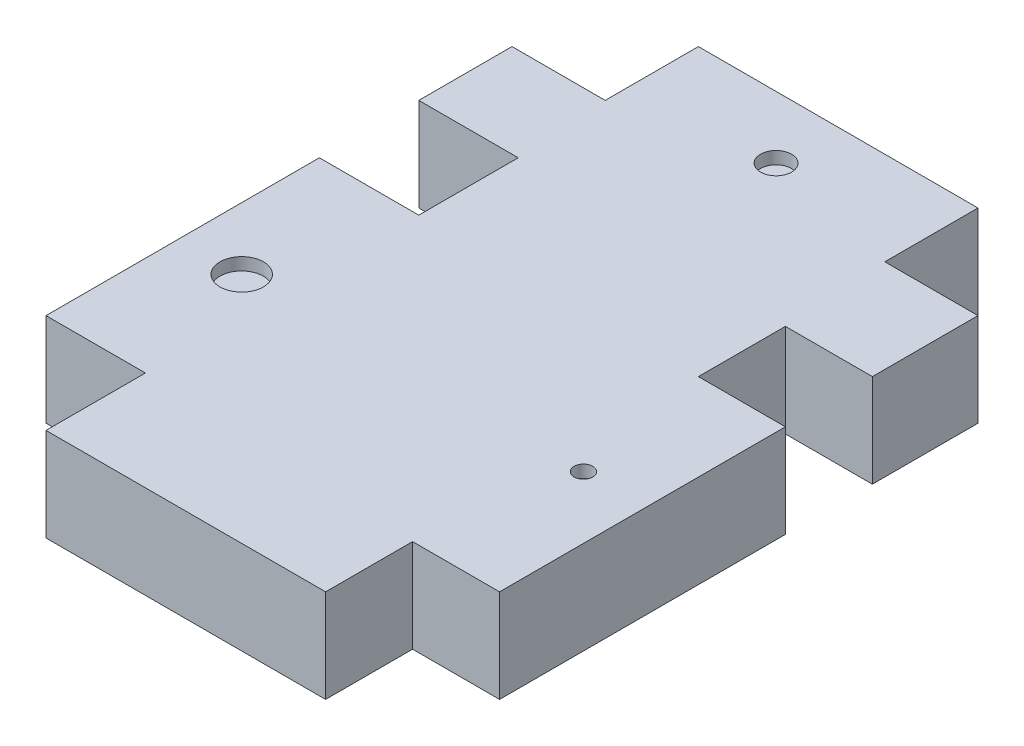
SolidWorks part; units mm, degrees
ref_plane "Front Plane" through (0, 0, 0) normal (0, 0, 1) x (1, 0, 0)
ref_plane "Top Plane" through (0, 0, 0) normal (0, 1, 0) x (1, 0, 0)
ref_plane "Right Plane" through (0, 0, 0) normal (1, 0, 0) x (0, 0, -1)
sketch "Sketch1" plane through (0, 0, 0) normal (0, 1, 0) x (1, 0, 0)
  line L0 (9.525, 67.31) -> (-85.725, 67.31)
  line L4 (-85.725, 67.31) -> (-85.725, -67.31)
  line L5 (-85.725, -67.31) -> (9.525, -67.31)
  line L6 (9.525, -67.31) -> (9.525, 67.31)
  line L7 (-85.725, 67.31) -> (-66.675, 67.31)
  line L8 (-85.725, 67.31) -> (-85.725, 48.26)
  line L9 (-85.725, 48.26) -> (-66.675, 48.26)
  line L10 (-66.675, 67.31) -> (-66.675, 48.26)
  line L11 (-9.525, 67.31) -> (9.525, 67.31)
  line L12 (-9.525, 67.31) -> (-9.525, 48.26)
  line L13 (-9.525, 48.26) -> (9.525, 48.26)
  line L14 (9.525, 67.31) -> (9.525, 48.26)
  line L23 (-85.725, -67.31) -> (-65.405, -67.31)
  line L24 (-85.725, -67.31) -> (-85.725, -46.99)
  line L25 (-85.725, -46.99) -> (-65.405, -46.99)
  line L26 (-65.405, -67.31) -> (-65.405, -46.99)
  line L27 (-85.725, 8.89) -> (-65.405, 8.89)
  line L28 (-85.725, 8.89) -> (-85.725, 29.21)
  line L29 (-85.725, 29.21) -> (-65.405, 29.21)
  line L30 (-65.405, 8.89) -> (-65.405, 29.21)
  line L44 (9.525, -67.31) -> (-8.255, -67.31)
  line L45 (9.525, -67.31) -> (9.525, -49.53)
  line L46 (9.525, -49.53) -> (-8.255, -49.53)
  line L47 (-8.255, -67.31) -> (-8.255, -49.53)
  line L48 (9.525, 8.89) -> (-8.255, 8.89)
  line L49 (9.525, 8.89) -> (9.525, 26.67)
  line L50 (9.525, 26.67) -> (-8.255, 26.67)
  line L51 (-8.255, 8.89) -> (-8.255, 26.67)
  point P0 (0, 0)
  point P18 (0, 48.26)
  dimension "D1" = 19.05
  dimension "D2" = 76.2
  dimension "D3" = 17.78
  dimension "D4" = 20.32
  dimension "D5" = 20.32
  dimension "D6" = 76.2
  dimension "D8" = 76.2
  dimension "D9" = 19.05
extrude "Boss-Extrude1" add sketch "Sketch1" along normal blind 19.05
sketch "Sketch2" plane through (0, 19.05, 0) normal (0, 1, 0) x (1, 0, 0)
  line L0 (-85.725, 8.89) -> (-65.405, 8.89) construction
  line L1 (-85.725, 8.89) -> (-85.725, -46.99) construction
  line L2 (9.525, -49.53) -> (9.525, 8.89) construction
  line L3 (-9.525, 67.31) -> (-66.675, 67.31) construction
  line L4 (-9.525, 67.31) -> (-9.525, 48.26) construction
  circle A0 centre (-3.175, -19.685) radius 1.905
  circle A1 centre (-73.025, -19.685) radius 4.445
  circle A2 centre (-38.1, 54.61) radius 3.175
  point P6 (0, 0)
  dimension "D1" = 6.35
  dimension "D2" = 3.81
  dimension "D3" = 8.89
  dimension "D4" = 28.575
  dimension "D5" = 12.7
  dimension "D6" = 12.7
  dimension "D7" = 12.7
  dimension "D8" = 28.575
extrude "Cut-Extrude1" cut sketch "Sketch2" against normal blind 2.54
